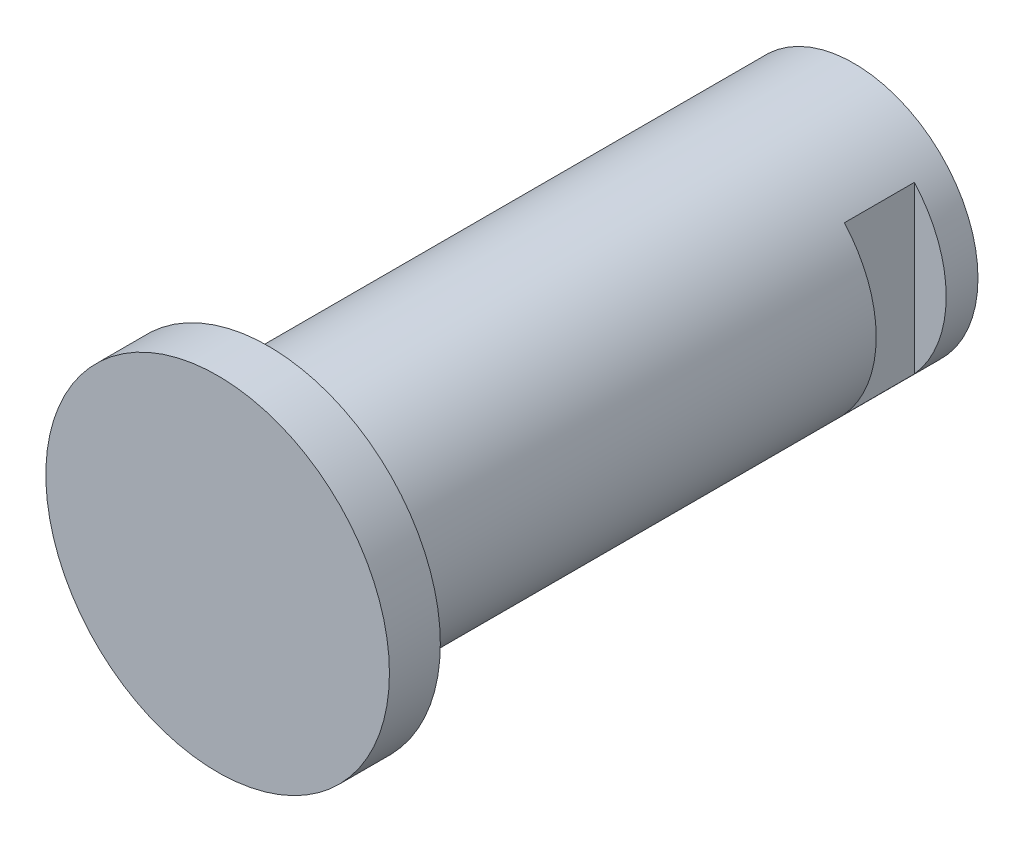
SolidWorks part; units mm, degrees
ref_plane "Front Plane" through (0, 0, 0) normal (0, 0, 1) x (1, 0, 0)
ref_plane "Top Plane" through (0, 0, 0) normal (0, 1, 0) x (1, 0, 0)
ref_plane "Right Plane" through (0, 0, 0) normal (1, 0, 0) x (0, 0, -1)
sketch "Sketch1" plane through (0, 0, 0) normal (0, 0, 1) x (1, 0, 0)
  circle A0 centre (0, 0) radius 4.953
  dimension "D1" = 9.906
extrude "Boss-Extrude1" add sketch "Sketch1" along normal blind 25.4
sketch "Sketch2" plane through (0, 0, 25.4) normal (0, 0, 1) x (1, 0, 0)
  circle A0 centre (0, 0) radius 6.858
  circle A1 centre (0, 0) radius 4.953 construction
  dimension "D1" = 1.905
extrude "Boss-Extrude2" add sketch "Sketch2" against normal blind 2.032
sketch "Sketch3" plane through (0, 0, 0) normal (0, 1, 0) x (1, 0, 0)
  line L0 (-4.953, 0) -> (-4.953, -23.368) construction
  line L1 (-4.953, -1.27) -> (4.953, -1.27)
  line L2 (-4.953, -1.27) -> (-4.953, -4.064)
  line L3 (-4.953, -4.064) -> (4.953, -4.064)
  line L4 (4.953, -1.27) -> (4.953, -4.064)
  line L5 (4.953, -23.368) -> (4.953, 0) construction
  line L6 (4.953, 0) -> (-4.953, 0) construction
  line L7 (-3.683, -1.27) -> (3.683, -1.27)
  line L8 (-3.683, -1.27) -> (-3.683, -4.064)
  line L9 (-3.683, -4.064) -> (3.683, -4.064)
  line L10 (3.683, -1.27) -> (3.683, -4.064)
  dimension "D1" = 1.27
  dimension "D2" = 2.794
  dimension "D3" = 1.27
  dimension "D4" = 1.27
extrude "Cut-Extrude1" cut sketch "Sketch3" against normal through all and the other way through all contours L1 L10 L3 L4 | L8 L1 L2 L3
